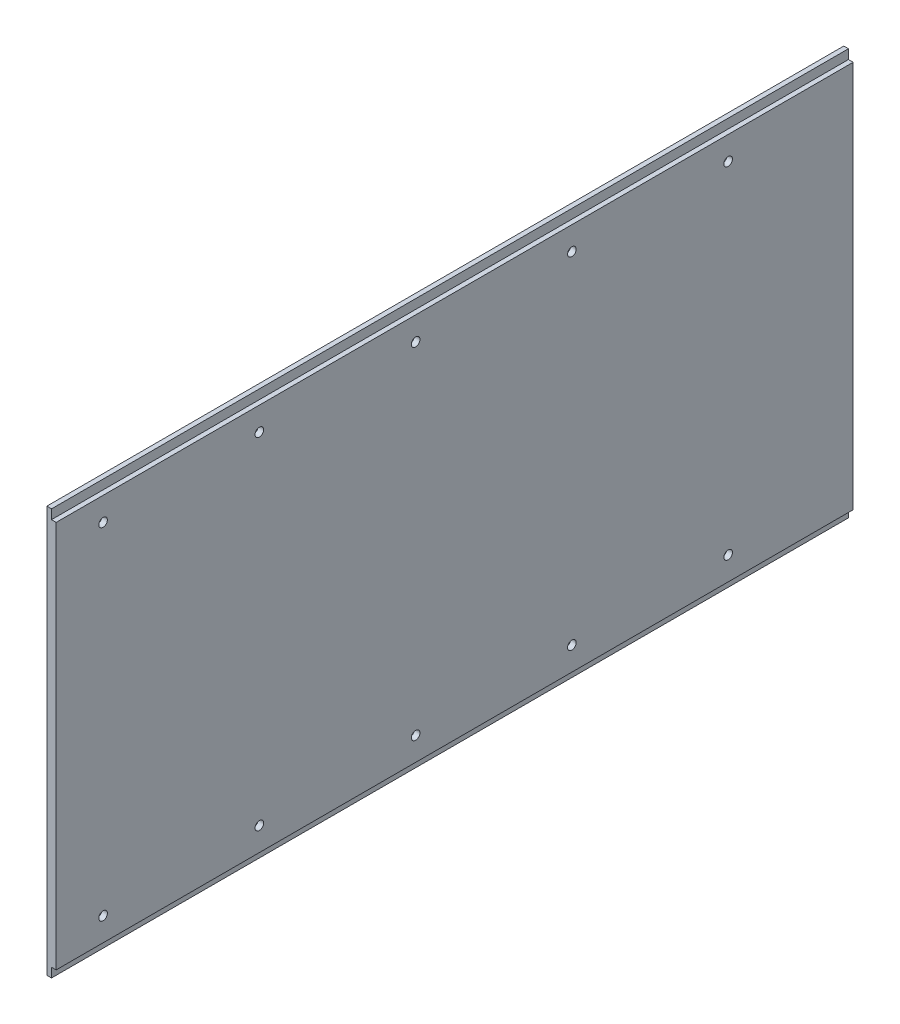
SolidWorks part; units mm, degrees
material "1060 Legierung"
ref_plane "Front Plane" through (0, 0, 0) normal (0, 0, 1) x (1, 0, 0)
ref_plane "Top Plane" through (0, 0, 0) normal (0, 1, 0) x (1, 0, 0)
ref_plane "Right Plane" through (0, 0, 0) normal (1, 0, 0) x (0, 0, -1)
sketch "Sketch1" plane through (0, 0, 0) normal (1, 0, 0) x (0, 0, -1)
  line L0 (0, 0) -> (59.3183, 0) construction
  line L1 (0, 28.1909) -> (0, -28.8956) construction
  line L2 (-255, 130) -> (255, 130)
  line L3 (255, 130) -> (255, -130)
  line L4 (255, -130) -> (-255, -130)
  line L5 (-255, -130) -> (-255, 130)
  dimension "D1" = 510
  dimension "D2" = 260
extrude "Boss-Extrude1" add sketch "Sketch1" along normal blind 6
sketch "Skizze2" plane through (0, 0, 255) normal (0, 0, 1) x (1, 0, 0)
  line L0 (21.4169, 0) -> (-13.9476, 0) construction
  line L1 (3, 130) -> (3, 124)
  line L2 (6, -130) -> (3, -130)
  line L3 (6, -130) -> (6, -124)
  line L4 (6, -124) -> (3, -124)
  line L5 (3, -130) -> (3, -124)
  line L6 (6, 124) -> (3, 124)
  line L7 (6, 130) -> (6, 124)
  line L8 (6, 130) -> (3, 130)
  dimension "D1" = 6
  dimension "D2" = 3
extrude "Schnitt-Linear austragen1" cut sketch "Skizze2" against normal through all
hole_wizard "CSK for M5 Countersunk Raised Head Screw1" positions "Sketch3" profile "Sketch2" countersink size "M5" standard "DIN" end condition through all
sketch "Sketch3" plane through (0, 0, 0) normal (-1, 0, 0) x (0, 0, 1)
  line L0 (255, -130) -> (-255, -130) construction
  line L2 (255, 130) -> (255, -130) construction
  point P0 (225, -109)
  dimension "D1" = 21
  dimension "D2" = 30
sketch "Sketch2" plane through (0, -109, 225) normal (0, 1, 0) x (0, 0, 1)
  line L0 (0, 0) -> (0, 6)
  line L1 (0, 6) -> (2.75, 6)
  line L2 (2.75, 6) -> (2.75, 2.45)
  line L3 (2.75, 2.45) -> (5.2, 0)
  line L5 (5.2, 0) -> (0, 0)
  line L6 (-2.75, 2.45) -> (-5.2, 0) construction
  line L11 (0, -6.35) -> (0, 107.95) construction
  dimension "Thru Hole Dia." = 5.5
  dimension "Thru Hole Depth" = 6
  dimension "Near C'Sink Dia." = 10.4
  dimension "Near C'Sink Angle" = 90
pattern_linear "LPattern1" count 5 spacing 100 along (0, 0, -1) of "CSK for M5 Countersunk Raised Head Screw1"
mirror "Mirror1" about plane through (0, 0, 0) normal (0, 1, 0) of "LPattern1", "CSK for M5 Countersunk Raised Head Screw1"
